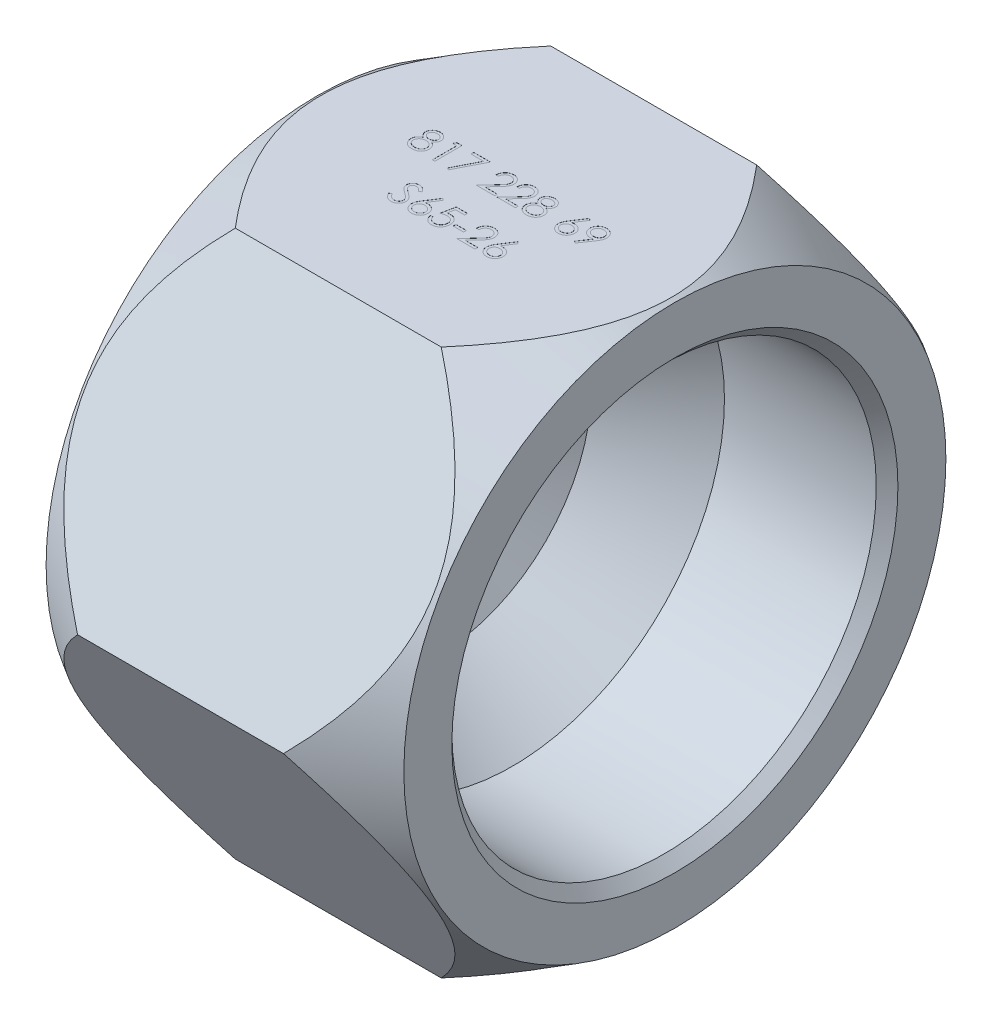
SolidWorks part; units mm, degrees
material "Plain Carbon Steel"
ref_plane "Front Plane" through (0, 0, 0) normal (0, 0, 1) x (1, 0, 0)
ref_plane "Top Plane" through (0, 0, 0) normal (0, 1, 0) x (1, 0, 0)
ref_plane "Right Plane" through (0, 0, 0) normal (1, 0, 0) x (0, 0, -1)
sketch "Sketch1" plane through (0, 0, 0) normal (0, 0, 1) x (1, 0, 0)
  line L0 (0, 0) -> (82.389, 0) construction
  line L1 (0, 0) -> (0, 25)
  line L2 (0, 25) -> (7, 29.1)
  line L3 (7, 29.1) -> (26, 29.1)
  line L4 (26, 29.1) -> (33, 25)
  line L5 (33, 25) -> (33, 19.575)
  line L6 (33, 19.575) -> (18, 19.575)
  line L7 (18, 19.575) -> (11, 14.3001)
  line L9 (0, 0) -> (3, 0)
  line L10 (11, 14.3001) -> (3, 0)
  dimension "D2" = 22
  dimension "D3" = 50
  dimension "D4" = 33
  dimension "D5" = 58.2
  dimension "D7" = 7
  dimension "D6" = 7
  dimension "D8" = 39.15
  dimension "D9" = 15
  dimension "D10" = 30
  dimension "D11" = 50
  dimension "D12" = 37
revolve "Revolve1" add sketch "Sketch1" angle 360 about L0
cosmetic thread "Cosmetic Thread1" parameters "D1"=13, "D2"=41
sketch "Sketch2" plane through (33, 0, 0) normal (1, 0, 0) x (0, 0, -1)
  line L1 (14.55, 25.2013) -> (-14.55, 25.2013)
  line L2 (-14.55, 25.2013) -> (-29.1, 0)
  line L3 (-29.1, 0) -> (-14.55, -25.2013)
  line L4 (-14.55, -25.2013) -> (14.55, -25.2013)
  line L5 (14.55, -25.2013) -> (29.1, 0)
  line L6 (29.1, 0) -> (14.55, 25.2013)
  circle A0 centre (0, 0) radius 25.2013 construction
  circle A1 centre (0, 0) radius 29.1 construction
extrude "Extrude1" cut sketch "Sketch2" against normal up to surface (33 mm away) flip side to cut up to face at (0, 0, 25)
chamfer "Chamfer1" distance 1 angle 45 1 edges at (33, 0, 19.575)
sketch "Sketch3" plane through (0, 25.2013, 0) normal (0, 1, 0) x (1, 0, 0)
  line L0 (0, 0) -> (33, 0) construction
  line L1 (33, -25) -> (33, 25) construction
  text T0 "817 228 69\r\nS65-26"
extrude "Cut-Extrude1" cut sketch "Sketch3" against normal blind 0.01
